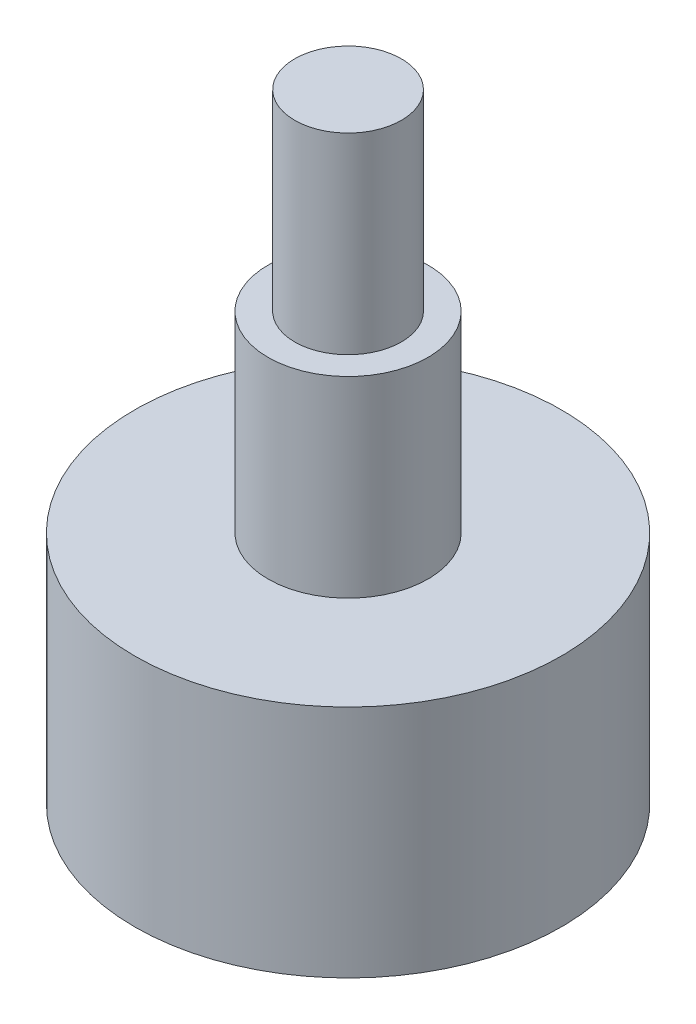
SolidWorks part; units mm, degrees
ref_plane "Front Plane" through (0, 0, 0) normal (0, 0, 1) x (1, 0, 0)
ref_plane "Top Plane" through (0, 0, 0) normal (0, 1, 0) x (1, 0, 0)
ref_plane "Right Plane" through (0, 0, 0) normal (1, 0, 0) x (0, 0, -1)
sketch "Sketch1" plane through (0, 0, 0) normal (0, 1, 0) x (1, 0, 0)
  circle A0 centre (0, 0) radius 12.7
extrude "Boss-Extrude1" add sketch "Sketch1" along normal blind 13.97
sketch "Sketch2" plane through (0, 13.97, 0) normal (0, 1, 0) x (1, 0, 0)
  circle A0 centre (0, 0) radius 4.7625
extrude "Boss-Extrude2" add sketch "Sketch2" along normal blind 11.43
sketch "Sketch3" plane through (0, 25.4, 0) normal (0, 1, 0) x (1, 0, 0)
  circle A0 centre (0, 0) radius 3.175
extrude "Boss-Extrude3" add sketch "Sketch3" along normal blind 11.43
